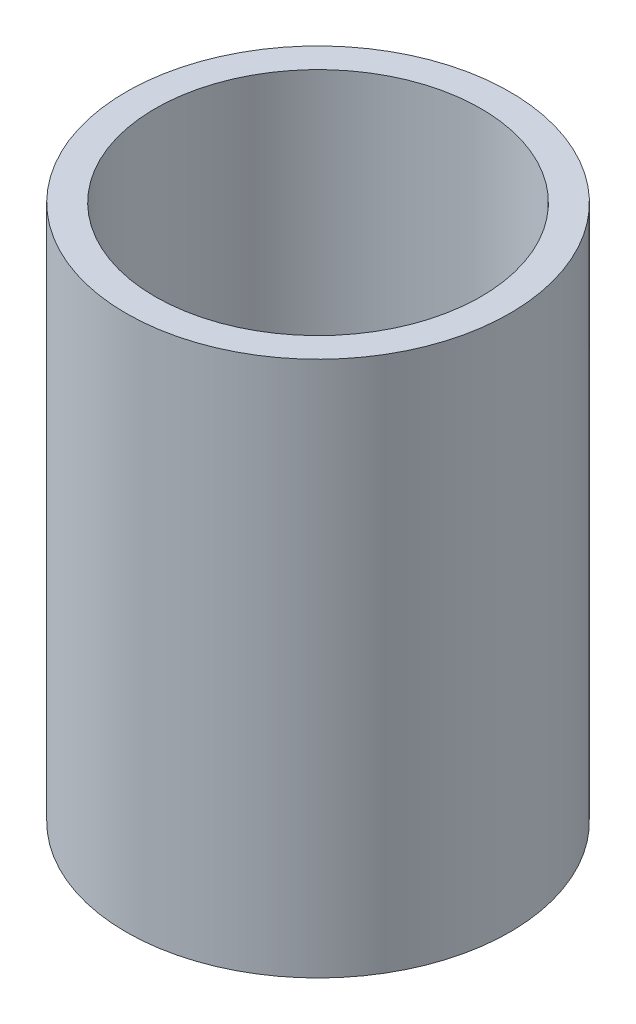
SolidWorks part; units mm, degrees
ref_plane "Front Plane" through (0, 0, 0) normal (0, 0, 1) x (1, 0, 0)
ref_plane "Top Plane" through (0, 0, 0) normal (0, 1, 0) x (1, 0, 0)
ref_plane "Right Plane" through (0, 0, 0) normal (1, 0, 0) x (0, 0, -1)
sketch "Sketch1" plane through (0, 0, 0) normal (0, 1, 0) x (1, 0, 0)
  line L0 (0, 11.25) -> (0, 13.25) construction
  circle A0 centre (0, 0) radius 11.25
  circle A1 centre (0, 0) radius 13.25
  dimension "D1" = 22.5
  dimension "D2" = 2
extrude "Boss-Extrude1" add sketch "Sketch1" along normal blind 37
